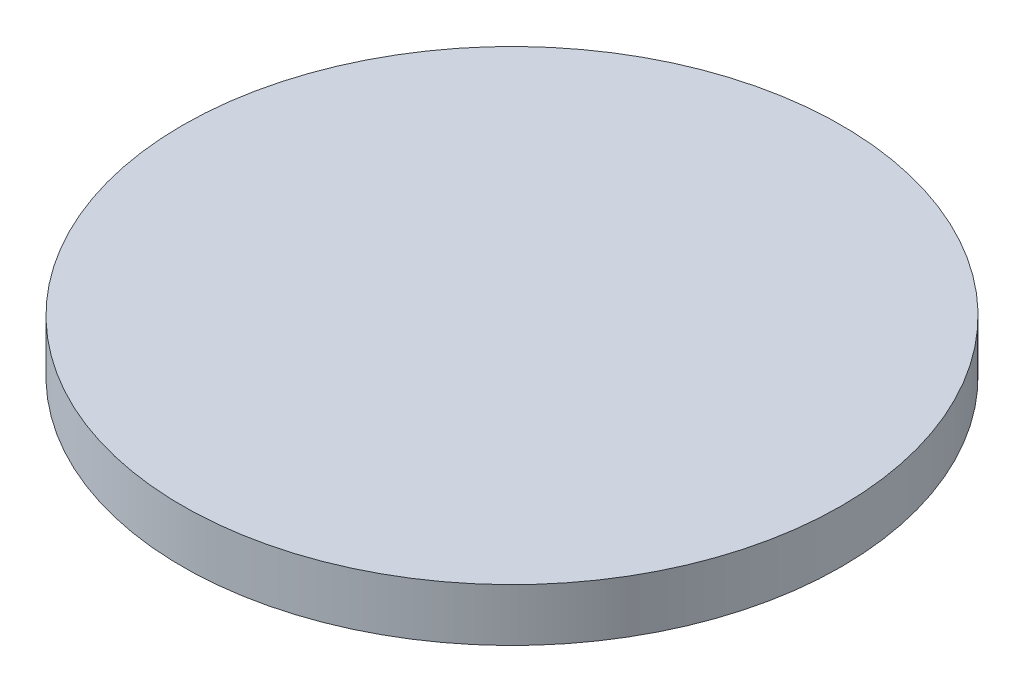
SolidWorks part; units mm, degrees
ref_plane "Front Plane" through (0, 0, 0) normal (0, 0, 1) x (1, 0, 0)
ref_plane "Top Plane" through (0, 0, 0) normal (0, 1, 0) x (1, 0, 0)
ref_plane "Right Plane" through (0, 0, 0) normal (1, 0, 0) x (0, 0, -1)
sketch "Sketch1" plane through (0, 0, 0) normal (0, 0, 1) x (1, 0, 0)
  line L0 (0, 0) -> (0, 4)
  line L1 (-25, 4) -> (0, 4)
  line L2 (-25, 4) -> (-25, 0)
  line L3 (-25, 0) -> (0, 0)
  line L4 (0, 4) -> (0, 0) construction
  line L5 (-25, 4) -> (0, 0) construction
  line L6 (-25, 0) -> (0, 4) construction
  point P0 (-12.5, 2)
  point P5 (0, 0)
  dimension "D1" = 4
  dimension "D2" = 25
revolve "Revolve1" add sketch "Sketch1" angle 360 about L0
